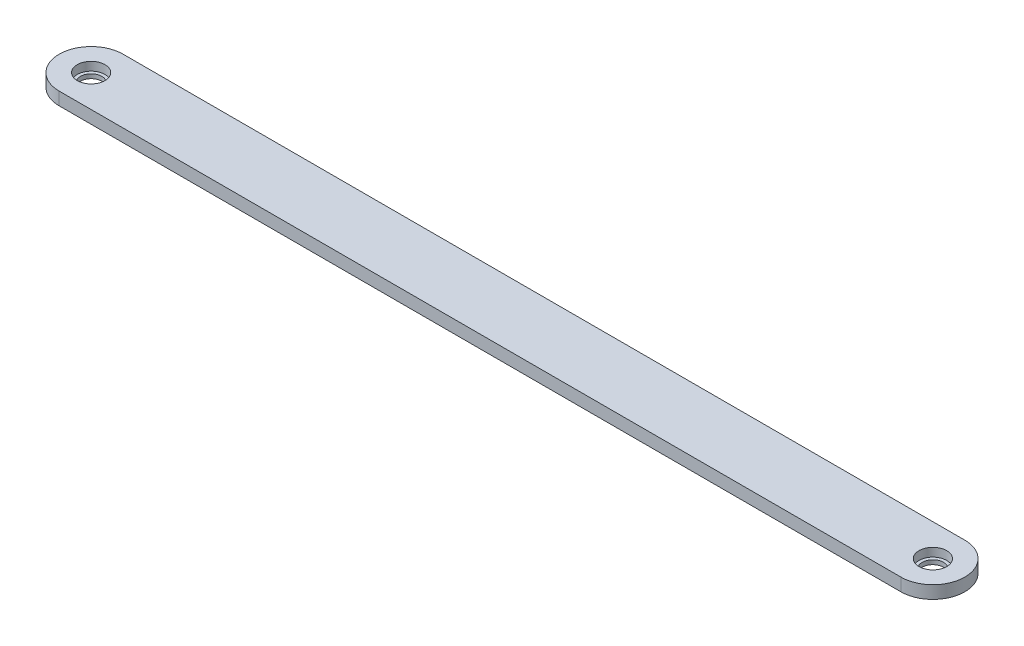
SolidWorks part; units mm, degrees
ref_plane "Front Plane" through (0, 0, 0) normal (0, 0, 1) x (1, 0, 0)
ref_plane "Top Plane" through (0, 0, 0) normal (0, 1, 0) x (1, 0, 0)
ref_plane "Right Plane" through (0, 0, 0) normal (1, 0, 0) x (0, 0, -1)
sketch "Sketch2" plane through (0, 0, 0) normal (0, 1, 0) x (1, 0, 0)
  line L1 (-45, 15) -> (350, 15)
  line L3 (-45, -15) -> (350, -15)
  arc A0 (-45, 15) -> (-45, -15) centre (-45, 0) ccw
  arc A1 (350, -15) -> (350, 15) centre (350, 0) ccw
  circle A2 centre (-45, 0) radius 5
  circle A3 centre (350, 0) radius 5
  point P0 (0, 0)
extrude "Boss-Extrude1" add sketch "Sketch2" along normal blind 6
sketch "Sketch4" plane through (0, 6, 0) normal (0, 1, 0) x (1, 0, 0)
  circle A0 centre (-45, 0) radius 6.5
  circle A1 centre (350, 0) radius 6.5
extrude "Cut-Extrude2" cut sketch "Sketch4" against normal blind 4
